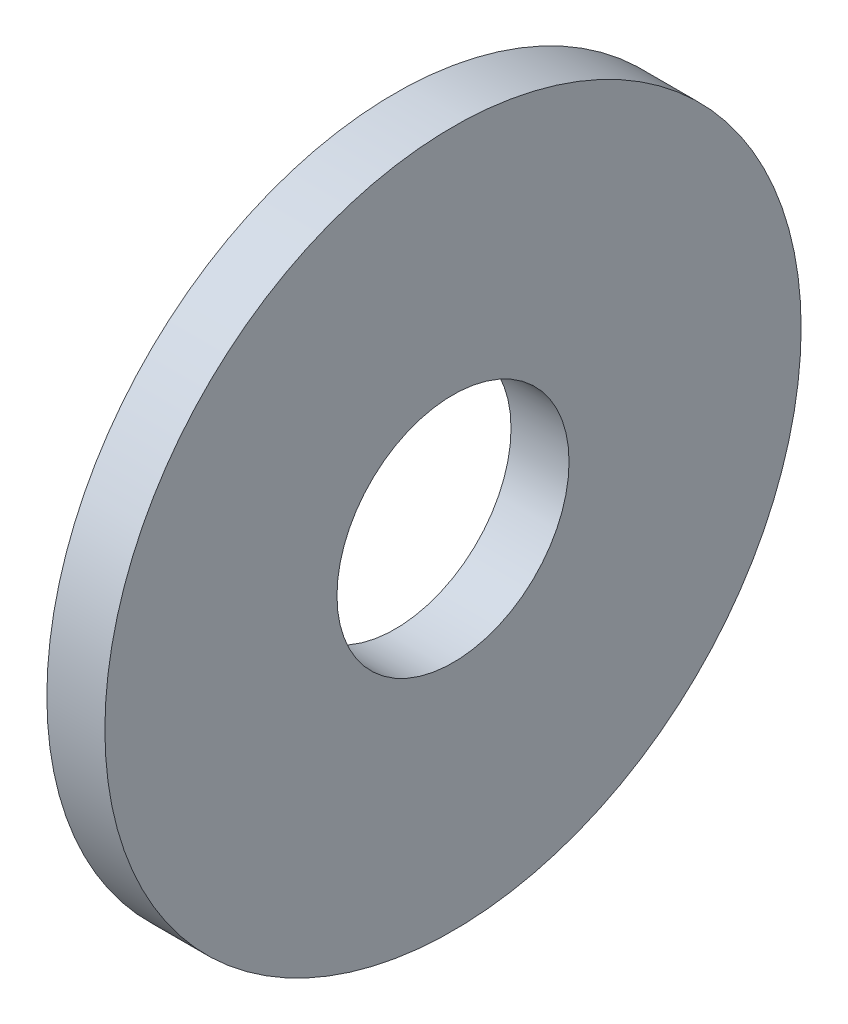
SolidWorks part; units mm, degrees
ref_plane "Front Plane" through (0, 0, 0) normal (0, 0, 1) x (1, 0, 0)
ref_plane "Top Plane" through (0, 0, 0) normal (0, 1, 0) x (1, 0, 0)
ref_plane "Right Plane" through (0, 0, 0) normal (1, 0, 0) x (0, 0, -1)
sketch "Sketch1" plane through (0, 0, 0) normal (1, 0, 0) x (0, 0, -1)
  circle A0 centre (0, 0) radius 6.35
  circle A1 centre (0, 0) radius 19.05
  dimension "D1" = 12.7
  dimension "D2" = 12.7
extrude "Boss-Extrude1" add sketch "Sketch1" along normal blind 3.175
